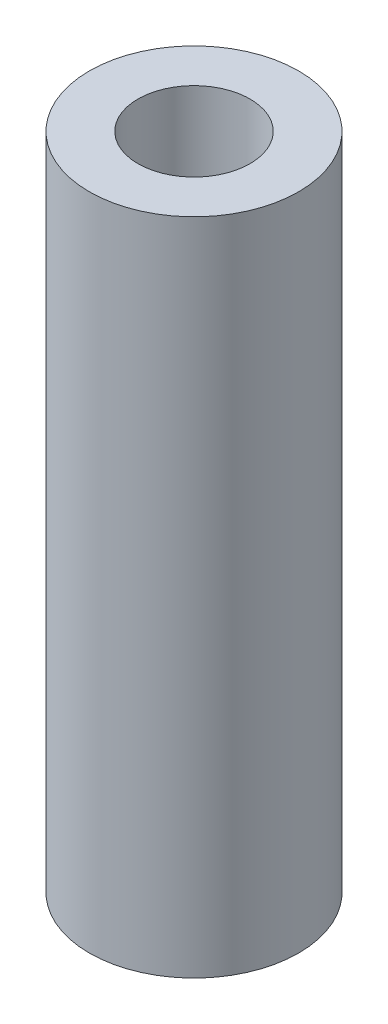
SolidWorks part; units mm, degrees
material "Delrin 2700 NC010, Low Viscosity Acetal Copolymer (SS)"
ref_plane "Front Plane" through (0, 0, 0) normal (0, 0, 1) x (1, 0, 0)
ref_plane "Top Plane" through (0, 0, 0) normal (0, 1, 0) x (1, 0, 0)
ref_plane "Right Plane" through (0, 0, 0) normal (1, 0, 0) x (0, 0, -1)
sketch "Sketch1" plane through (0, 0, 0) normal (0, 1, 0) x (1, 0, 0)
  circle A0 centre (0, 0) radius 3.175
extrude "Boss-Extrude1" add sketch "Sketch1" along normal blind 20
hole_wizard "M3 Clearance Hole1" positions "Sketch2" profile "Sketch3" hole size "M3" standard "ANSI Metric" end condition through all
sketch "Sketch2" plane through (0, 20, 0) normal (0, 1, 0) x (1, 0, 0)
  point P0 (0, 0)
sketch "Sketch3" plane through (0, 20, 0) normal (1, 0, 0) x (0, 0, 1)
  line L0 (0, 0) -> (0, 20)
  line L1 (0, 20) -> (1.7, 20)
  line L2 (1.7, 20) -> (1.7, 0)
  line L5 (1.7, 0) -> (0, 0)
  line L11 (0, -6.35) -> (0, 107.95) construction
  dimension "Thru Hole Dia." = 3.4
  dimension "Thru Hole Depth" = 20
